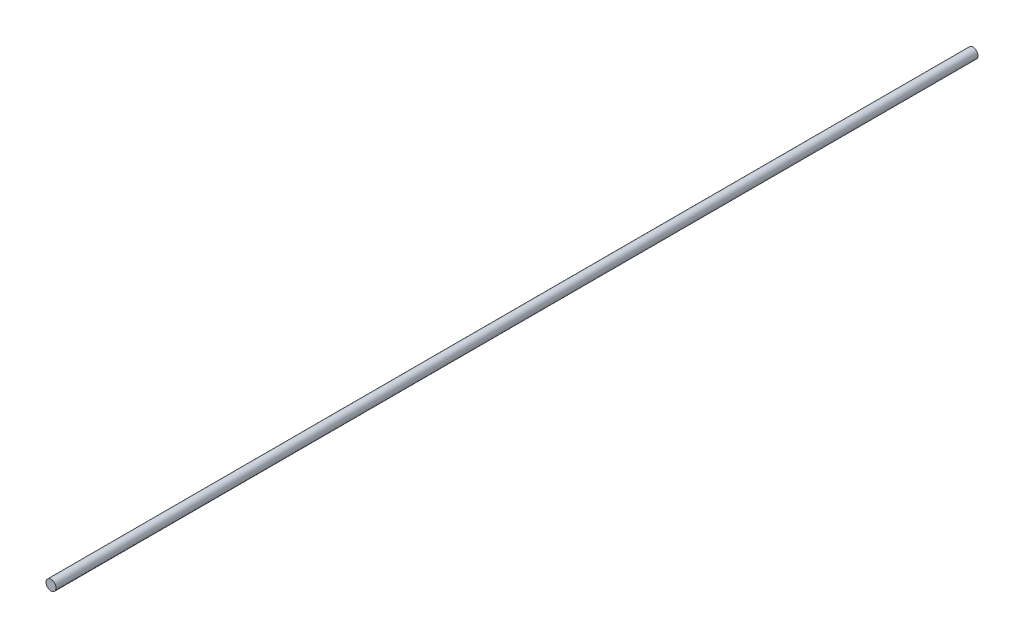
SolidWorks part; units mm, degrees
ref_plane "前视基准面" through (0, 0, 0) normal (0, 0, 1) x (1, 0, 0)
ref_plane "上视基准面" through (0, 0, 0) normal (0, 1, 0) x (1, 0, 0)
ref_plane "右视基准面" through (0, 0, 0) normal (1, 0, 0) x (0, 0, -1)
other "Configuration Table"
sketch "草图1" plane through (0, 0, 0) normal (0, 0, 1) x (1, 0, 0)
  circle A0 centre (0, 0) radius 2
  dimension "diameter" = 4
extrude "Driver_power_cable_envelope" add sketch "草图1" along normal blind 367.6044
